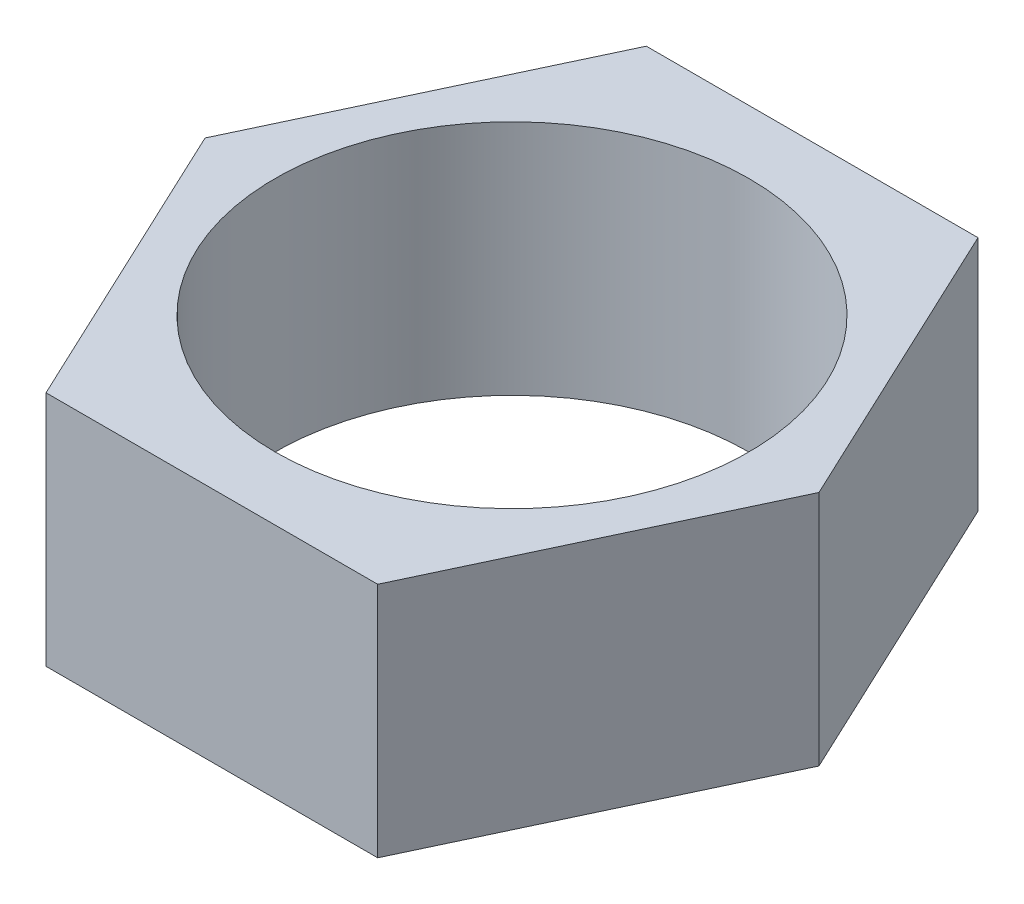
SolidWorks part; units mm, degrees
ref_plane "前视基准面" through (0, 0, 0) normal (0, 0, 1) x (1, 0, 0)
ref_plane "上视基准面" through (0, 0, 0) normal (0, 1, 0) x (1, 0, 0)
ref_plane "右视基准面" through (0, 0, 0) normal (1, 0, 0) x (0, 0, -1)
other "Configuration Table"
sketch "草图1" plane through (0, 0, 0) normal (0, 1, 0) x (1, 0, 0)
  line L0 (-3.5, 6.3348) -> (3.5, 6.3348)
  line L1 (3.5, 6.3348) -> (6.4783, 0)
  line L2 (6.4783, 0) -> (3.5, -6.3348)
  line L3 (3.5, -6.3348) -> (-3.5, -6.3348)
  line L4 (-3.5, -6.3348) -> (-6.4783, 0)
  line L5 (-6.4783, 0) -> (-3.5, 6.3348)
  line L6 (-6.4783, 0) -> (6.4783, 0)
  point P5 (0, 0)
  dimension "D1" = 7
extrude "凸台-拉伸1" add sketch "草图1" along normal blind 5 contours L6 L4 L3 L2 | L5 L6 L1 L0
ref_plane "基准面1" through (0, 5, 0) normal (0, 1, 0) x (1, 0, 0)
sketch "草图2" plane through (0, 5, 0) normal (0, 1, 0) x (1, 0, 0)
  circle A0 centre (0, 0) radius 5
  dimension "D1" = 10
extrude "切除-拉伸1" cut sketch "草图2" against normal up to next
cosmetic thread "装饰螺纹线1" parameters "D2"=11
